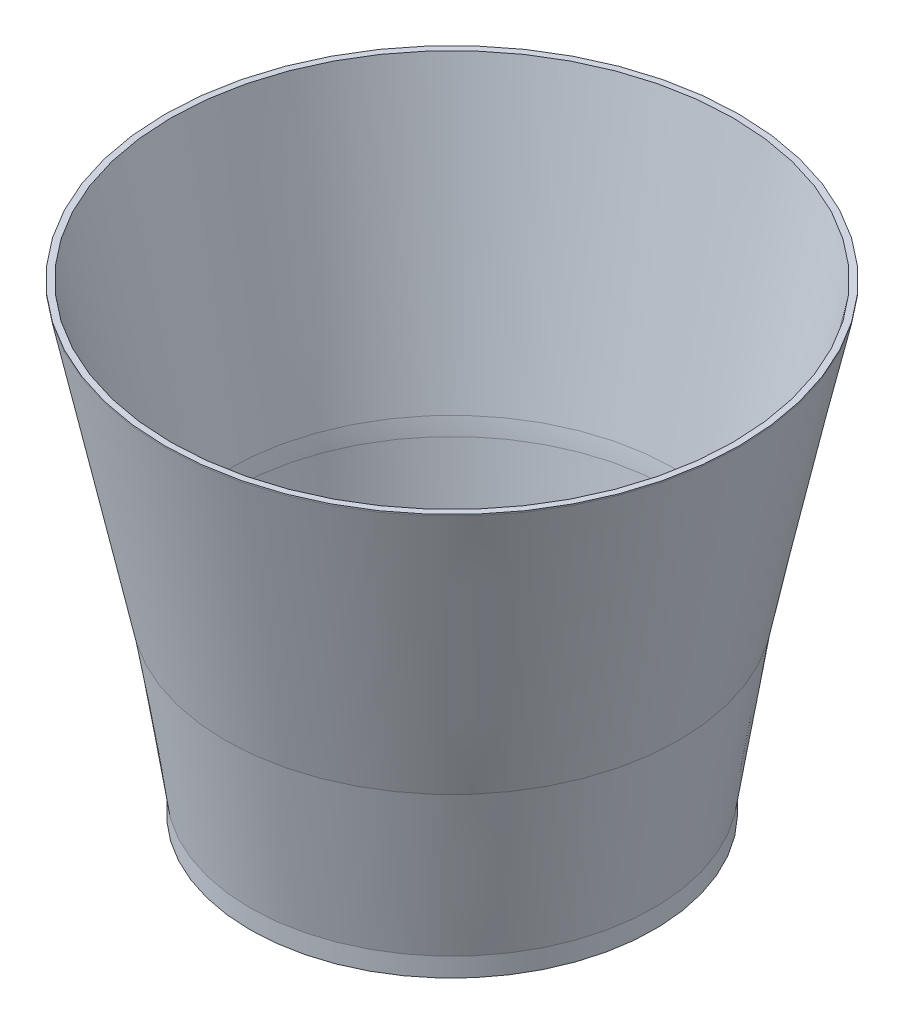
SolidWorks part; units mm, degrees
ref_plane "Front Plane" through (0, 0, 0) normal (0, 0, 1) x (1, 0, 0)
ref_plane "Top Plane" through (0, 0, 0) normal (0, 1, 0) x (1, 0, 0)
ref_plane "Right Plane" through (0, 0, 0) normal (1, 0, 0) x (0, 0, -1)
sketch "Sketch1" plane through (0, 0, 0) normal (0, 1, 0) x (1, 0, 0)
  circle A0 centre (0, 0) radius 32
  circle A1 centre (0, 10) radius 2
  circle A2 centre (0, -5) radius 2
  circle A4 centre (0, 21.1624) radius 4
  circle A5 centre (16.5454, 13.1945) radius 4
  circle A6 centre (20.6318, -4.7091) radius 4
  circle A7 centre (9.182, -19.0667) radius 4
  circle A8 centre (-9.182, -19.0667) radius 4
  circle A9 centre (-20.6318, -4.7091) radius 4
  circle A10 centre (-16.5454, 13.1945) radius 4
  point P26 (0, 0)
  dimension "D1" = 64
  dimension "D2" = 7
extrude "Boss-Extrude1" add sketch "Sketch1" along normal blind 3
sketch "Sketch3" plane through (0, 0, 0) normal (1, 0, 0) x (0, 0, -1)
  line L0 (-32, 3) -> (-35.9596, 28)
  line L1 (0, 0) -> (0, 36.9962) construction
  line L2 (-31, 3) -> (32, 3) construction
  line L3 (-35.9596, 28) -> (-34.9596, 28)
  line L4 (-34.9596, 28) -> (-30.5248, 0)
  line L5 (-30.5248, 0) -> (-32, 0)
  line L6 (-32, 0) -> (-32, 3)
  line L7 (32, 3) -> (-32, 3) construction
  dimension "D1" = 99
  dimension "D2" = 25
  dimension "D3" = 1
revolve "Revolve2" add sketch "Sketch3" angle 360 about L1
sketch "Sketch5" plane through (0, 0, 0) normal (1, 0, 0) x (0, 0, -1)
  line L0 (-35.9596, 28) -> (-45.5247, 73)
  line L1 (-34.9815, 28.2079) -> (-44.5465, 73.2079)
  line L2 (-32, 3) -> (-44.5945, 82.5186) construction
  line L3 (-35.9596, 28) -> (-34.9596, 28)
  line L4 (-34.9596, 28) -> (-34.9815, 28.2079)
  line L5 (-44.5465, 73.2079) -> (-45.5247, 73.2079)
  line L6 (-45.5247, 73.2079) -> (-45.5247, 73)
  dimension "D1" = 3
  dimension "D2" = 45
  dimension "D3" = 1
revolve "Revolve3" add sketch "Sketch5" angle 360 about L1
fillet "Fillet1" radius 50 1 edges at (0, 28.2079, -34.9815)
